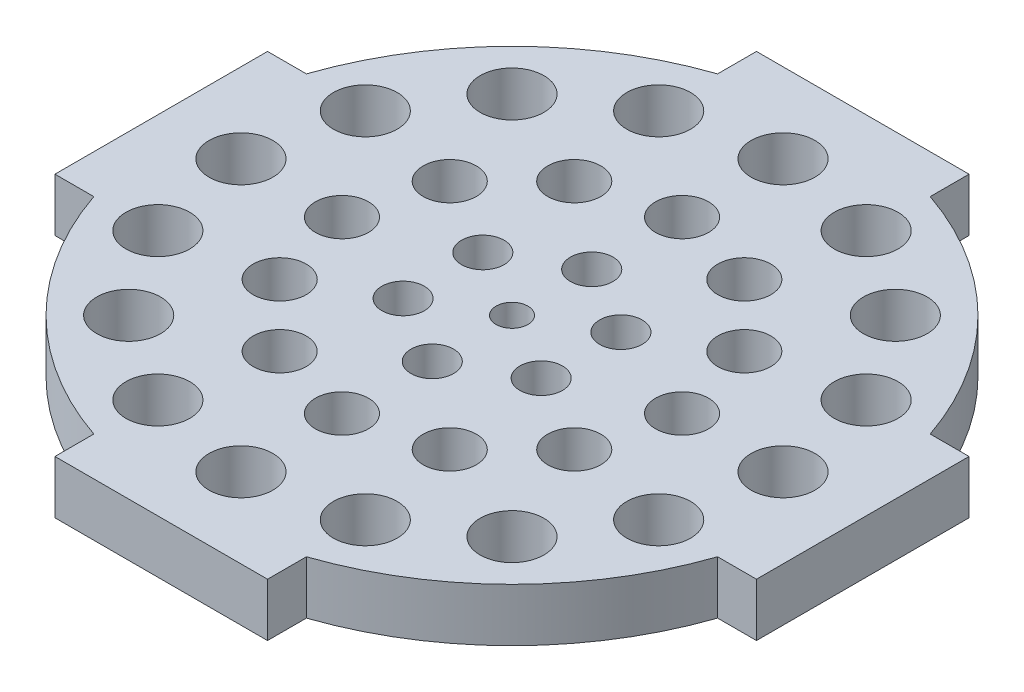
SolidWorks part; units mm, degrees
ref_plane "Front Plane" through (0, 0, 0) normal (0, 0, 1) x (1, 0, 0)
ref_plane "Top Plane" through (0, 0, 0) normal (0, 1, 0) x (1, 0, 0)
ref_plane "Right Plane" through (0, 0, 0) normal (1, 0, 0) x (0, 0, -1)
sketch "Sketch1" plane through (0, 0, 0) normal (0, 1, 0) x (1, 0, 0)
  line L1 (16.5, 5) -> (-16.5, 5)
  line L2 (16.5, 5) -> (16.5, -5)
  line L3 (16.5, -5) -> (-16.5, -5)
  line L4 (-16.5, 5) -> (-16.5, -5)
  line L5 (16.5, 5) -> (-16.5, -5) construction
  line L6 (16.5, -5) -> (-16.5, 5) construction
  line L7 (5, 16.5) -> (-5, 16.5)
  line L8 (5, 16.5) -> (5, -16.5)
  line L9 (5, -16.5) -> (-5, -16.5)
  line L10 (-5, 16.5) -> (-5, -16.5)
  line L11 (5, 16.5) -> (-5, -16.5) construction
  line L12 (5, -16.5) -> (-5, 16.5) construction
  circle A0 centre (0, 0) radius 15.5
  dimension "D1" = 31
  dimension "D2" = 10
  dimension "D3" = 33
  dimension "D4" = 33
  dimension "D5" = 10
extrude "Boss-Extrude1" add sketch "Sketch1" along normal blind 2.5 contours L1 L10 L3 L8 | L1 A0 L3 L10 | L10 A0 L1 | L8 A0 L10 L1 | L1 A0 L8 | L3 A0 L1 L8 | A0 L3 L2 L1 | L8 A0 L3 | L10 A0 L8 L3 | L3 A0 L10 | A0 L1 L4 L3 | A0 L10 L9 L8 | A0 L8 L7 L10
sketch "Sketch2" plane through (0, 2.5, 0) normal (0, 1, 0) x (1, 0, 0)
  line L0 (0, 2.75) -> (0, 0.75) construction
  line L1 (0, 6.75) -> (0, 4.75) construction
  line L2 (0, 11.25) -> (0, 9.25) construction
  circle A0 centre (0, 0) radius 0.75
  circle A1 centre (0, 3.75) radius 1
  circle A2 centre (0, 8) radius 1.25
  circle A3 centre (0, 12.75) radius 1.5
  circle A4 centre (3.2476, 1.875) radius 1
  circle A5 centre (3.2476, -1.875) radius 1
  circle A6 centre (0, -3.75) radius 1
  circle A7 centre (-3.2476, -1.875) radius 1
  circle A8 centre (-3.2476, 1.875) radius 1
  circle A9 centre (4, 6.9282) radius 1.25
  circle A10 centre (6.9282, 4) radius 1.25
  circle A11 centre (8, 0) radius 1.25
  circle A12 centre (6.9282, -4) radius 1.25
  circle A13 centre (4, -6.9282) radius 1.25
  circle A14 centre (0, -8) radius 1.25
  circle A15 centre (-4, -6.9282) radius 1.25
  circle A16 centre (-6.9282, -4) radius 1.25
  circle A17 centre (-8, 0) radius 1.25
  circle A18 centre (-6.9282, 4) radius 1.25
  circle A19 centre (-4, 6.9282) radius 1.25
  circle A20 centre (4.8792, 11.7795) radius 1.5
  circle A21 centre (9.0156, 9.0156) radius 1.5
  circle A22 centre (11.7795, 4.8792) radius 1.5
  circle A23 centre (12.75, 0) radius 1.5
  circle A24 centre (11.7795, -4.8792) radius 1.5
  circle A25 centre (9.0156, -9.0156) radius 1.5
  circle A26 centre (4.8792, -11.7795) radius 1.5
  circle A27 centre (0, -12.75) radius 1.5
  circle A28 centre (-4.8792, -11.7795) radius 1.5
  circle A29 centre (-9.0156, -9.0156) radius 1.5
  circle A30 centre (-11.7795, -4.8792) radius 1.5
  circle A31 centre (-12.75, 0) radius 1.5
  circle A32 centre (-11.7795, 4.8792) radius 1.5
  circle A33 centre (-9.0156, 9.0156) radius 1.5
  circle A34 centre (-4.8792, 11.7795) radius 1.5
  dimension "D1" = 1.5
  dimension "D2" = 2
  dimension "D3" = 2.5
  dimension "D4" = 3
  dimension "D8" = 6
  dimension "D5" = 2
  dimension "D6" = 2
  dimension "D7" = 2
  dimension "D9" = 12
  dimension "D10" = 16
extrude "Cut-Extrude1" cut sketch "Sketch2" against normal through all
